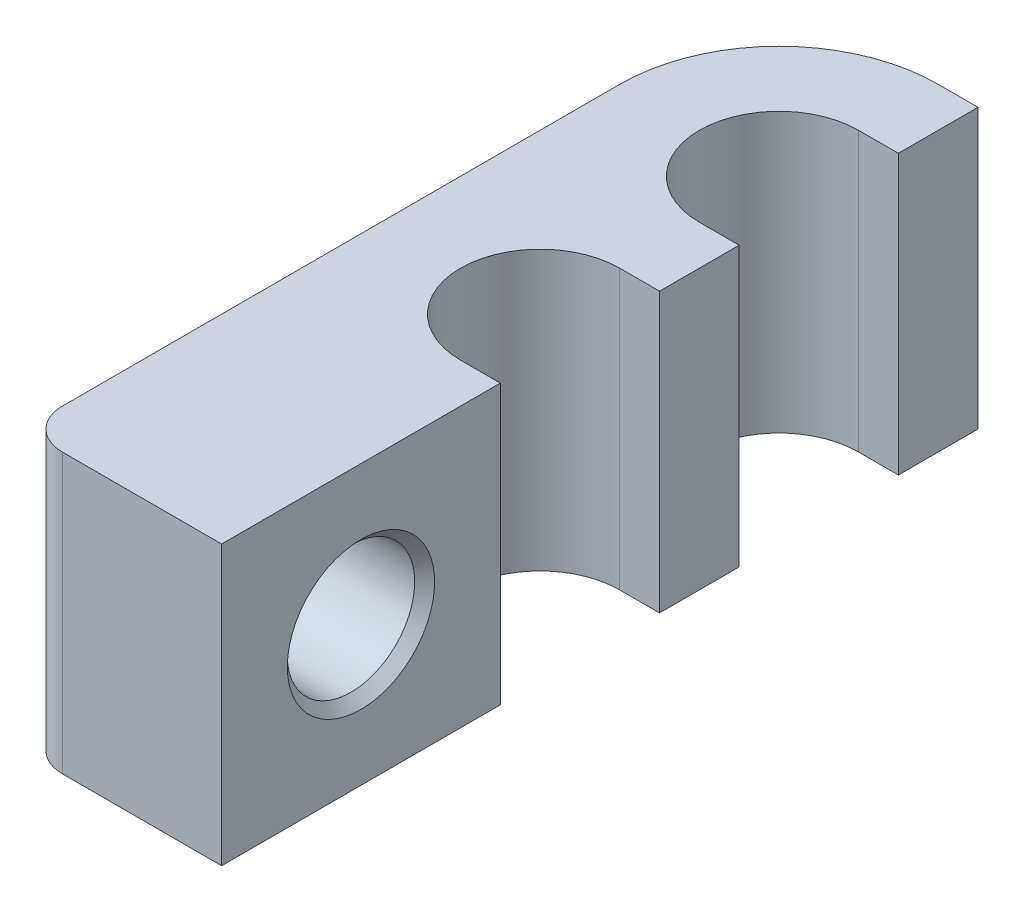
SolidWorks part; units mm, degrees
material "ABS"
ref_plane "Front Plane" through (0, 0, 0) normal (0, 0, 1) x (1, 0, 0)
ref_plane "Top Plane" through (0, 0, 0) normal (0, 1, 0) x (1, 0, 0)
ref_plane "Right Plane" through (0, 0, 0) normal (1, 0, 0) x (0, 0, -1)
sketch "Sketch1" plane through (0, 0, 0) normal (0, 1, 0) x (1, 0, 0)
  line L0 (0, 0) -> (-5, 0)
  line L1 (-5, 0) -> (-5, 9)
  line L2 (0, 13) -> (0, 11)
  line L3 (0, 0) -> (0, 7)
  line L4 (0, 2) -> (-5, 2) construction
  line L5 (0, 5) -> (-5, 5) construction
  line L6 (-5, 7) -> (-8, 7) construction
  line L7 (-8, 7) -> (-8, 0) construction
  line L8 (-8, 0) -> (-5, 0) construction
  line L9 (-2.5, 5) -> (-2.5, 2) construction
  line L10 (0, 11) -> (-1, 11)
  line L11 (-1, 7) -> (0, 7)
  line L13 (0, 3.5) -> (-5, 3.5) construction
  line L14 (0, 13) -> (-1, 13)
  line L15 (-1, 17) -> (0, 17)
  line L16 (0, 17) -> (0, 19)
  line L17 (0, 19) -> (-1, 19)
  line L18 (-5, 15) -> (-5, 9)
  arc A2 (-1, 11) -> (-1, 7) centre (-1, 9) ccw
  arc A4 (-1, 13) -> (-1, 17) centre (-1, 15) cw
  arc A5 (-1, 19) -> (-5, 15) centre (-1, 15) ccw
  point P19 (-8, 3.5)
  point P20 (-2.5, 3.5)
  point P28 (-2.5, 3.5)
  point P33 (0, 0)
  point P34 (0, 13)
  point P35 (-5.7919, 15)
  dimension "D1" = 2
  dimension "D2" = 2
  dimension "D3" = 3
  dimension "D4" = 7
  dimension "D5" = 3
  dimension "D6" = 1
  dimension "D7" = 3.5
  dimension "D8" = 3.5
extrude "Boss-Extrude1" add sketch "Sketch1" along normal blind 7
hole_wizard "M3 Clearance Hole1" positions "Sketch2" profile "Sketch3" hole size "M3" standard "ANSI Metric" end condition up to next
sketch "Sketch2" plane through (-5, 0, 0) normal (-1, 0, 0) x (0, 0, 1)
  line L0 (0, 0) -> (-7, 7) construction
  line L1 (-15, 7) -> (0, 7) construction
  line L2 (-7, 7) -> (0, 7) construction
  line L3 (0, 7) -> (0, 0) construction
  point P0 (-3.5, 3.5)
  point P14 (-3.5, 3.5)
sketch "Sketch3" plane through (-5, 3.5, -3.5) normal (0, 1, 0) x (0, 0, 1)
  line L0 (0, 0) -> (0, 5)
  line L1 (0, 5) -> (1.6, 5)
  line L2 (1.6, 5) -> (1.6, 0)
  line L5 (1.6, 0) -> (0, 0)
  line L11 (0, -6.35) -> (0, 107.95) construction
  dimension "Thru Hole Dia." = 3.2
  dimension "Thru Hole Depth" = 5
chamfer "Chamfer2" distance 0.25 angle 45 2 edges at (-5, 3.5, -1.9) (0, 3.5, -1.9)
fillet "Fillet1" radius 1 1 edges at (-5, 3.5, 0)
